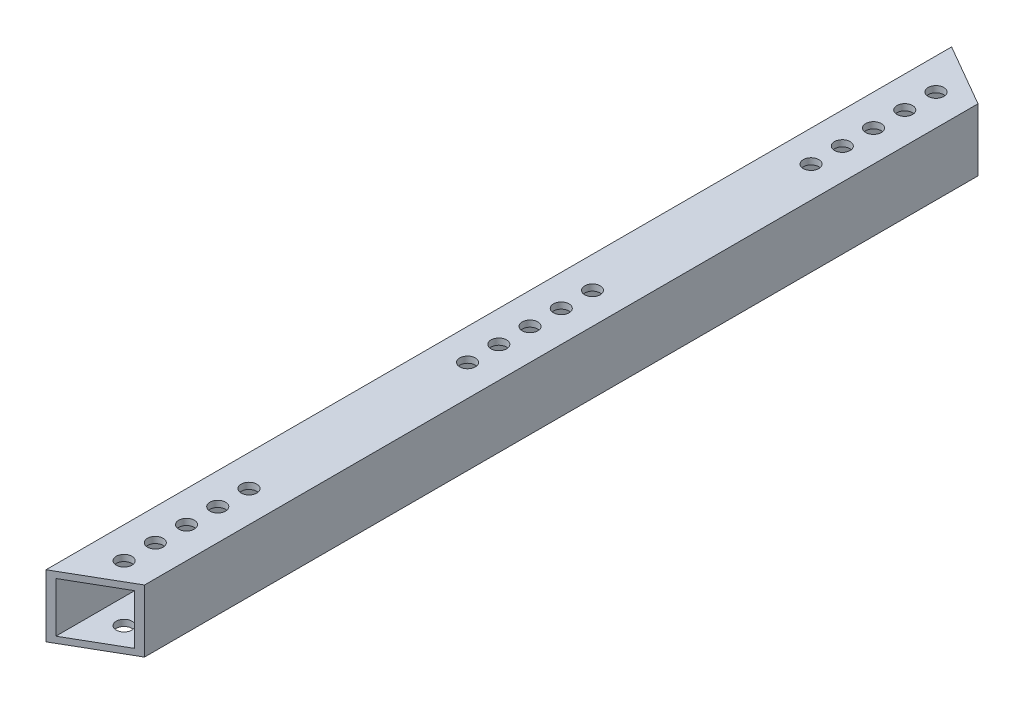
SolidWorks part; units mm, degrees
ref_plane "Front Plane" through (0, 0, 0) normal (0, 0, 1) x (1, 0, 0)
ref_plane "Top Plane" through (0, 0, 0) normal (0, 1, 0) x (1, 0, 0)
ref_plane "Right Plane" through (0, 0, 0) normal (1, 0, 0) x (0, 0, -1)
sketch "Sketch1" plane through (0, 0, 0) normal (0, 0, 1) x (1, 0, 0)
  line L0 (-10.16, 10.16) -> (10.16, 10.16)
  line L1 (-12.7, -12.7) -> (12.7, -12.7)
  line L2 (-12.7, -12.7) -> (-12.7, 12.7)
  line L3 (-12.7, 12.7) -> (12.7, 12.7)
  line L4 (12.7, -12.7) -> (12.7, 12.7)
  line L5 (-12.7, -12.7) -> (12.7, 12.7) construction
  line L6 (-12.7, 12.7) -> (12.7, -12.7) construction
  line L7 (10.16, -10.16) -> (10.16, 10.16)
  line L8 (-10.16, -10.16) -> (10.16, -10.16)
  line L9 (-10.16, -10.16) -> (-10.16, 10.16)
  point P0 (0, 0)
  dimension "D1" = 25.4
  dimension "D2" = 25.4
  dimension "D3" = 2.54
extrude "Boss-Extrude2" add sketch "Sketch1" along normal blind 368.3
sketch "Sketch2" plane through (0, 12.7, 0) normal (0, 1, 0) x (1, 0, 0)
  line L0 (-12.7, -368.3) -> (12.7, -353.6353)
  line L1 (12.7, -368.3) -> (12.7, 0) construction
  line L2 (12.7, -353.6353) -> (12.7, -368.3)
  line L3 (12.7, -368.3) -> (-12.7, -368.3)
  line L4 (-12.7, -184.15) -> (12.7, -184.15) construction
  line L5 (-12.7, -368.3) -> (-12.7, 0) construction
  line L6 (12.7, 0) -> (-12.7, 0)
  line L7 (12.7, -14.6647) -> (12.7, 0)
  line L8 (-12.7, 0) -> (12.7, -14.6647)
  dimension "D1" = 30
extrude "Cut-Extrude1" cut sketch "Sketch2" against normal through all
sketch "Sketch3" plane through (0, 12.7, 0) normal (0, 1, 0) x (1, 0, 0)
  line L0 (0, -7.3323) -> (0, -360.9677) construction
  line L1 (-12.7, 0) -> (12.7, -14.6647) construction
  line L2 (12.7, -353.6353) -> (-12.7, -368.3) construction
  line L3 (12.7, -184.15) -> (-12.7, -184.15) construction
  line L4 (12.7, -353.6353) -> (12.7, -14.6647) construction
  line L5 (-12.7, -368.3) -> (-12.7, 0) construction
  circle A0 centre (0, -184.15) radius 3.175
  circle A1 centre (0, -171.45) radius 3.175
  circle A2 centre (0, -158.75) radius 3.175
  circle A3 centre (0, -209.55) radius 3.175
  circle A4 centre (0, -196.85) radius 3.175
  circle A5 centre (0, -349.25) radius 3.175
  circle A6 centre (0, -336.55) radius 3.175
  circle A7 centre (0, -323.85) radius 3.175
  circle A8 centre (0, -311.15) radius 3.175
  circle A9 centre (0, -298.45) radius 3.175
  circle A10 centre (0, -69.85) radius 3.175
  circle A11 centre (0, -57.15) radius 3.175
  circle A12 centre (0, -44.45) radius 3.175
  circle A13 centre (0, -31.75) radius 3.175
  circle A14 centre (0, -19.05) radius 3.175
  dimension "D1" = 6.35
  dimension "D3" = 6.35
  dimension "D4" = 165.1
  dimension "D2" = 3
  dimension "D5" = 5
extrude "Cut-Extrude2" cut sketch "Sketch3" against normal through all
